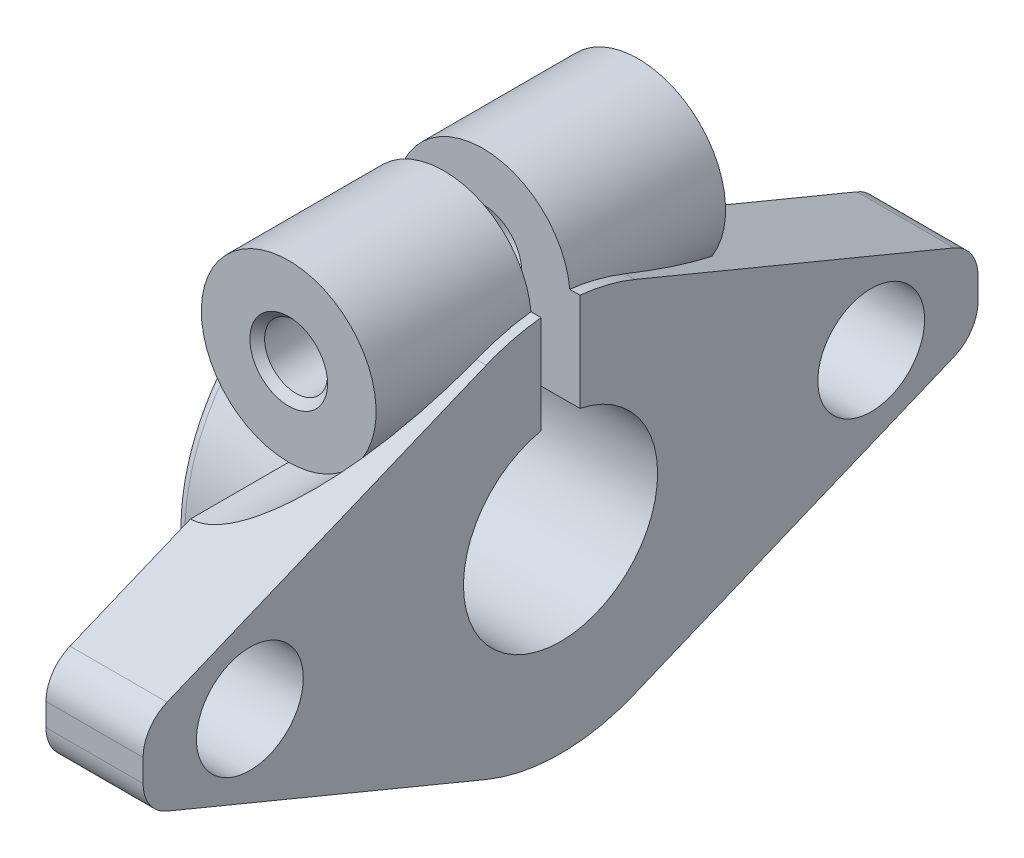
SolidWorks part; units mm, degrees
ref_plane "前基準面" through (0, 0, 0) normal (0, 0, 1) x (1, 0, 0)
ref_plane "上基準面" through (0, 0, 0) normal (0, 1, 0) x (1, 0, 0)
ref_plane "右基準面" through (0, 0, 0) normal (1, 0, 0) x (0, 0, -1)
ref_plane "平面1" through (0, 0, 0) normal (1, 0, 0) x (0, 0, -1)
sketch "草圖1" plane through (0, 0, 0) normal (1, 0, 0) x (0, 0, -1)
  line L0 (-21.5, 0.582) -> (-21.5, -0.582)
  line L1 (-20.2654, -2.4297) -> (-3.8268, -9.2388)
  line L2 (3.8268, -9.2388) -> (20.2654, -2.4297)
  line L3 (21.5, -0.582) -> (21.5, 0.582)
  line L4 (20.2654, 2.4297) -> (3.8268, 9.2388)
  line L5 (-3.8268, 9.2388) -> (-20.2654, 2.4297)
  arc A0 (-21.5, -0.582) -> (-20.2654, -2.4297) centre (-19.5, -0.582) ccw
  arc A1 (-3.8268, -9.2388) -> (0, -10) centre (0, 0) ccw
  arc A2 (0, -10) -> (3.8268, -9.2388) centre (0, 0) ccw
  arc A3 (20.2654, -2.4297) -> (21.5, -0.582) centre (19.5, -0.582) ccw
  arc A4 (21.5, 0.582) -> (20.2654, 2.4297) centre (19.5, 0.582) ccw
  arc A5 (3.8268, 9.2388) -> (0, 10) centre (0, 0) ccw
  arc A6 (0, 10) -> (-3.8268, 9.2388) centre (0, 0) ccw
  arc A7 (-20.2654, 2.4297) -> (-21.5, 0.582) centre (-19.5, 0.582) ccw
extrude "填料-伸長1" add sketch "草圖1" against normal blind 5
ref_plane "平面2" through (0, 0, 0) normal (0, 0, 1) x (1, 0, 0)
sketch "草圖2" plane through (0, 0, 0) normal (0, 0, 1) x (1, 0, 0)
  line L0 (-10, 0) -> (-10, 9.3348)
  line L1 (-9.5097, 9.8425) -> (-5, 10)
  line L2 (-5, 10) -> (-5, 0)
  line L3 (-5, 0) -> (-10, 0)
  line L4 (-5, 0) -> (-10, 0) construction
  arc A0 (-10, 9.3348) -> (-9.5097, 9.8425) centre (-9.492, 9.3348) cw
revolve "旋轉1" add sketch "草圖2" angle 360 about L4
ref_plane "平面3" through (0, 0, 0) normal (0, 0, 1) x (1, 0, 0)
sketch "草圖3" plane through (0, 0, 0) normal (0, 0, 1) x (1, 0, 0)
  circle A0 centre (-5, 9.5) radius 4.5
extrude "填料-伸長2" add sketch "草圖3" against normal blind 9 and the other way blind 9
ref_plane "平面4" through (0, 0, 9) normal (0, 0, 1) x (1, 0, 0)
sketch "草圖4" plane through (0, 0, 9) normal (0, 0, 1) x (1, 0, 0)
  line L0 (-10, 5) -> (-5, 5)
  line L1 (-9.5, 9.5) -> (-10, 9.5)
  line L2 (-10, 9.5) -> (-10, 5)
  arc A0 (-5, 5) -> (-9.5, 9.5) centre (-5, 9.5) ccw
extrude "除料-伸長1" cut sketch "草圖4" along normal blind 9
ref_plane "平面5" through (0, 0, 0) normal (1, 0, 0) x (0, 0, -1)
sketch "草圖5" plane through (0, 0, 0) normal (1, 0, 0) x (0, 0, -1)
  line L0 (-1, 0) -> (1, 0)
  line L1 (1, 0) -> (1, 24)
  line L2 (1, 24) -> (-1, 24)
  line L3 (-1, 24) -> (-1, 0)
extrude "除料-伸長2" cut sketch "草圖5" against normal blind 10
ref_plane "平面6" through (0, 0, 0) normal (0, 0, 1) x (1, 0, 0)
sketch "草圖6" plane through (0, 0, 0) normal (0, 0, 1) x (1, 0, 0)
  line L0 (-10, 0) -> (-10, 6)
  line L1 (-10, 6) -> (-8.5, 6)
  line L2 (-8.5, 6) -> (-8.5, 5)
  line L3 (-8.5, 5) -> (0, 5)
  line L4 (0, 5) -> (0, 0)
  line L5 (0, 0) -> (-10, 0)
  line L6 (0, 0) -> (-10, 0) construction
revolve "除料-旋轉1" cut sketch "草圖6" angle 360 about L6
ref_plane "平面7" through (-5, 0, 0) normal (1, 0, 0) x (0, 0, -1)
sketch "草圖7" plane through (-5, 0, 0) normal (1, 0, 0) x (0, 0, -1)
  line L0 (1, 9.5) -> (1, 11.5)
  line L1 (1, 11.5) -> (1.379, 11.121)
  line L2 (1.379, 11.121) -> (8.621, 11.121)
  line L3 (8.621, 11.121) -> (9.1, 11.6)
  line L4 (9.1, 11.6) -> (13.5, 11.6)
  line L5 (13.5, 11.6) -> (13.5, 9.5)
  line L6 (13.5, 9.5) -> (1, 9.5)
  line L7 (13.5, 9.5) -> (1, 9.5) construction
revolve "除料-旋轉2" cut sketch "草圖7" angle 360 about L7
cosmetic thread "裝飾螺紋線1" parameters "D1"=8, "D2"=4
ref_plane "平面8" through (-5, 0, 0) normal (1, 0, 0) x (0, 0, -1)
sketch "草圖8" plane through (-5, 0, 0) normal (1, 0, 0) x (0, 0, -1)
  line L0 (-9, 9.5) -> (-9, 11.5)
  line L1 (-9, 11.5) -> (-8.621, 11.121)
  line L2 (-8.621, 11.121) -> (-1.379, 11.121)
  line L3 (-1.379, 11.121) -> (-1, 11.5)
  line L4 (-1, 11.5) -> (-1, 9.5)
  line L5 (-1, 9.5) -> (-9, 9.5)
  line L6 (-1, 9.5) -> (-9, 9.5) construction
revolve "除料-旋轉3" cut sketch "草圖8" angle 360 about L6
cosmetic thread "裝飾螺紋線2" parameters "D1"=8, "D2"=4
ref_plane "平面9" through (0, 0, 0) normal (1, 0, 0) x (0, 0, -1)
sketch "草圖9" plane through (0, 0, 0) normal (1, 0, 0) x (0, 0, -1)
  circle A0 centre (16, 0) radius 2.75
extrude "除料-伸長3" cut sketch "草圖9" against normal blind 5
ref_plane "平面10" through (0, 0, 0) normal (1, 0, 0) x (0, 0, -1)
sketch "草圖10" plane through (0, 0, 0) normal (1, 0, 0) x (0, 0, -1)
  circle A0 centre (-16, 0) radius 2.75
extrude "除料-伸長4" cut sketch "草圖10" against normal blind 5
